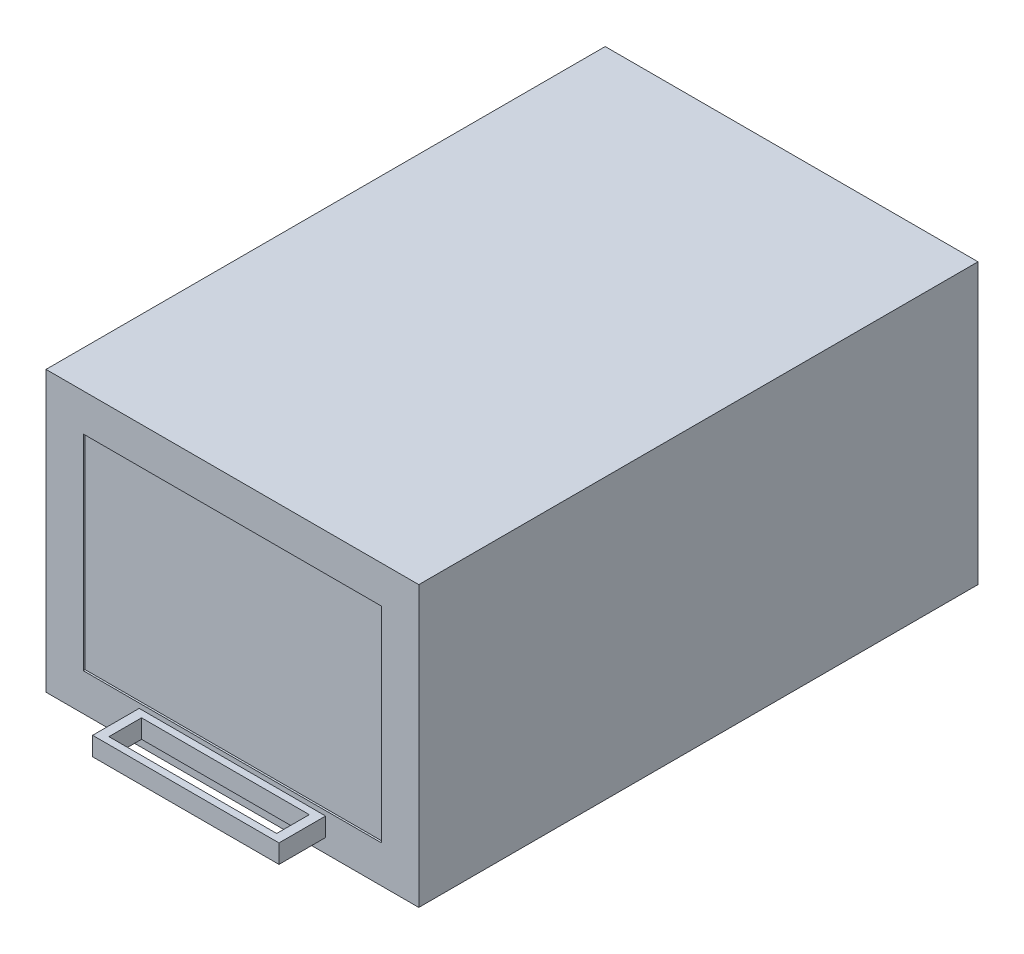
SolidWorks part; units mm, degrees
ref_plane "Спереди" through (0, 0, 0) normal (0, 0, 1) x (1, 0, 0)
ref_plane "Сверху" through (0, 0, 0) normal (0, 1, 0) x (1, 0, 0)
ref_plane "Справа" through (0, 0, 0) normal (1, 0, 0) x (0, 0, -1)
sketch "Эскиз1" plane through (0, 0, 0) normal (0, 1, 0) x (1, 0, 0)
  line L1 (0, 0) -> (-400, 0)
  line L2 (0, 0) -> (0, -600)
  line L3 (0, -600) -> (-400, -600)
  line L4 (-400, 0) -> (-400, -600)
  dimension "D1" = 400
  dimension "D2" = 600
extrude "Бобышка-Вытянуть1" add sketch "Эскиз1" along normal blind 300
sketch "Эскиз2" plane through (0, 0, 600) normal (0, 0, 1) x (1, 0, 0)
  line L1 (-300, 35) -> (-100, 35)
  line L2 (-300, 35) -> (-300, 15)
  line L3 (-300, 15) -> (-100, 15)
  line L4 (-100, 35) -> (-100, 15)
  line L5 (-400, 0) -> (0, 0) construction
  point P4 (-200, 15)
  point P7 (-200, 0)
  dimension "D1" = 200
  dimension "D2" = 15
  dimension "D3" = 20
extrude "Бобышка-Вытянуть2" add sketch "Эскиз2" along normal blind 50
sketch "Эскиз3" plane through (0, 35, 0) normal (0, 1, 0) x (1, 0, 0)
  line L0 (-300, -650) -> (-300, -600) construction
  line L1 (-290, -607.5) -> (-110, -607.5)
  line L2 (-290, -607.5) -> (-290, -642.5)
  line L3 (-290, -642.5) -> (-110, -642.5)
  line L4 (-110, -607.5) -> (-110, -642.5)
  line L5 (-100, -650) -> (-300, -650) construction
  point P6 (-300, -625)
  point P7 (-290, -625)
  point P8 (-200, -642.5)
  point P11 (-200, -650)
  dimension "D1" = 180
  dimension "D2" = 35
extrude "Вырез-Вытянуть1" cut sketch "Эскиз3" against normal blind 50
sketch "Эскиз4" plane through (0, 0, 600) normal (0, 0, 1) x (1, 0, 0)
  line L0 (-400, 300) -> (0, 300) construction
  line L1 (-360, 260) -> (-40, 260)
  line L2 (-360, 260) -> (-360, 40)
  line L3 (-360, 40) -> (-40, 40)
  line L4 (-40, 260) -> (-40, 40)
  line L5 (-400, 300) -> (-400, 0) construction
  point P4 (-200, 260)
  point P7 (-200, 300)
  point P8 (-360, 150)
  point P11 (-400, 150)
  dimension "D1" = 40
  dimension "D2" = 40
extrude "Вырез-Вытянуть2" cut sketch "Эскиз4" against normal blind 2
